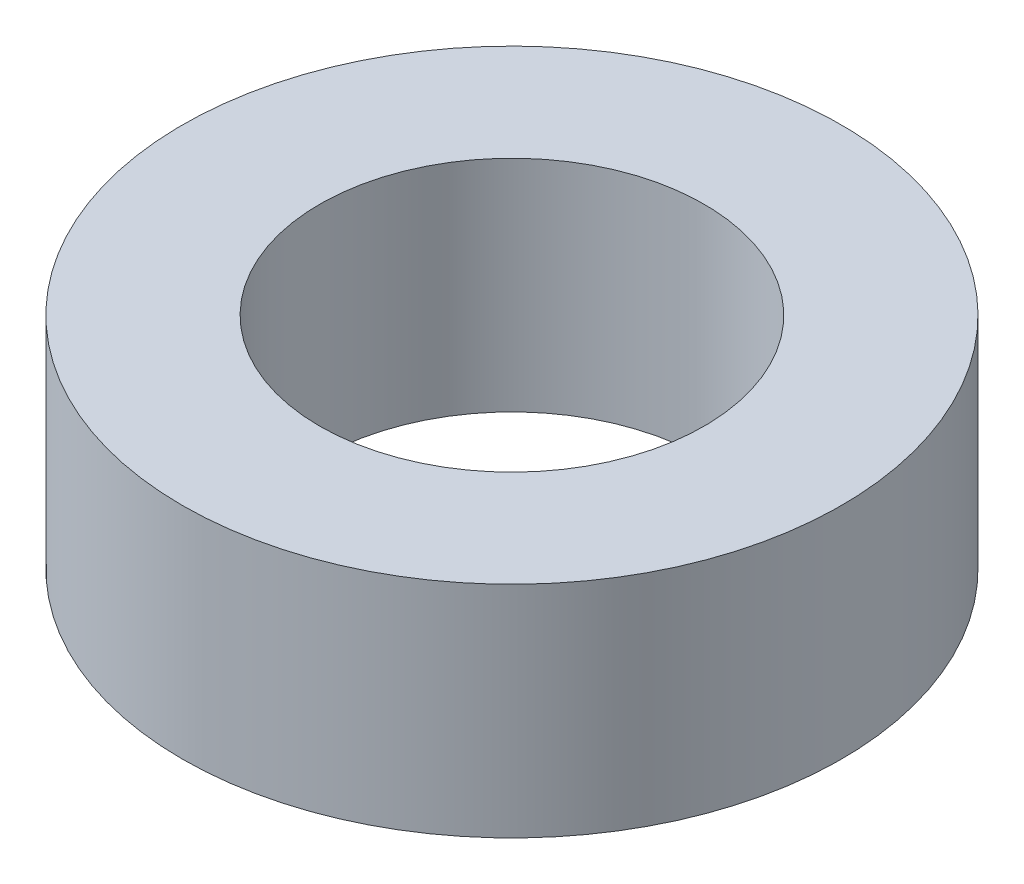
SolidWorks part; units mm, degrees
ref_plane "Front Plane" through (0, 0, 0) normal (0, 0, 1) x (1, 0, 0)
ref_plane "Top Plane" through (0, 0, 0) normal (0, 1, 0) x (1, 0, 0)
ref_plane "Right Plane" through (0, 0, 0) normal (1, 0, 0) x (0, 0, -1)
sketch "Sketch1" plane through (0, 0, 0) normal (0, 1, 0) x (1, 0, 0)
  circle A0 centre (0, 0) radius 1.75
  circle A1 centre (0, 0) radius 3
  dimension "D1" = 3.5
  dimension "D2" = 6
extrude "Boss-Extrude1" add sketch "Sketch1" along normal blind 2
